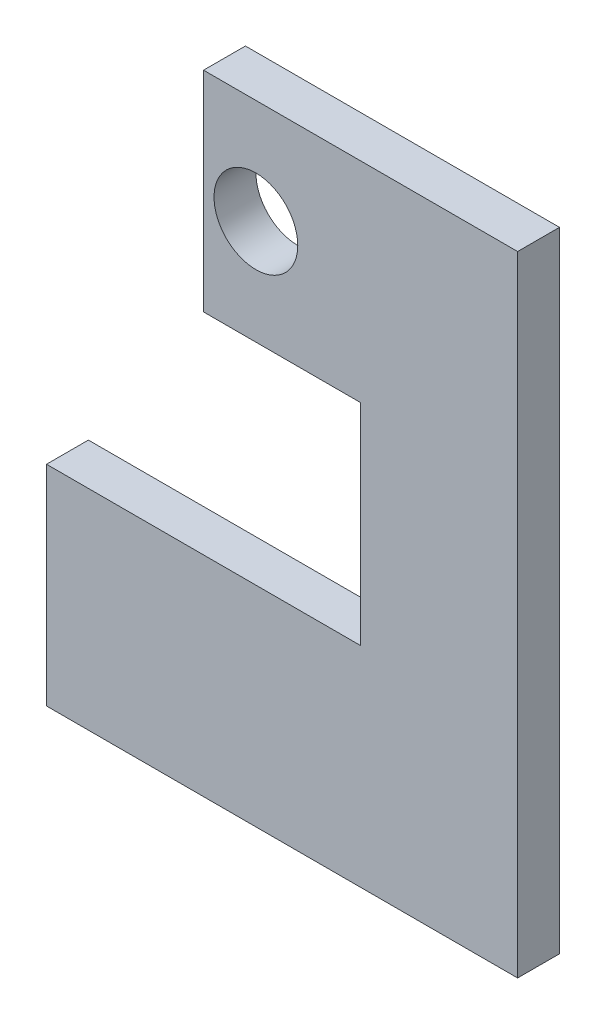
SolidWorks part; units mm, degrees
ref_plane "Front Plane" through (0, 0, 0) normal (0, 0, 1) x (1, 0, 0)
ref_plane "Top Plane" through (0, 0, 0) normal (0, 1, 0) x (1, 0, 0)
ref_plane "Right Plane" through (0, 0, 0) normal (1, 0, 0) x (0, 0, -1)
sketch "Sketch1" plane through (0, 0, 0) normal (0, 0, 1) x (1, 0, 0)
  line L1 (-75, 50) -> (75, 50)
  line L2 (-75, 50) -> (-75, -50)
  line L3 (-75, -50) -> (0, -50)
  line L4 (75, 50) -> (75, -50.7382)
  line L9 (0, -50) -> (0, -150.4884)
  line L10 (0, -150.4884) -> (-150, -150.4884)
  line L11 (-150, -150.4884) -> (-150, -250.4884)
  line L12 (-150, -250.4884) -> (75, -250.4884)
  line L13 (75, -250.4884) -> (75, -50.7382)
  circle A0 centre (-50, 0) radius 20
  dimension "D5" = 40
  dimension "D1" = 100
  dimension "D2" = 150
  dimension "D3" = 75
  dimension "D4" = 50
  dimension "D6" = 25
  dimension "D7" = 100
  dimension "D8" = 225
extrude "Boss-Extrude2" add sketch "Sketch1" along normal blind 20
